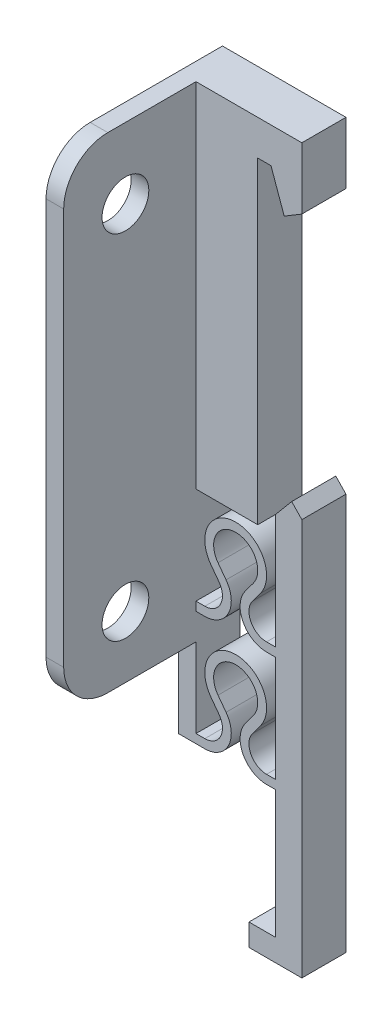
SolidWorks part; units mm, degrees
ref_plane "Front Plane" through (0, 0, 0) normal (0, 0, 1) x (1, 0, 0)
ref_plane "Top Plane" through (0, 0, 0) normal (0, 1, 0) x (1, 0, 0)
ref_plane "Right Plane" through (0, 0, 0) normal (1, 0, 0) x (0, 0, -1)
sketch "Sketch1" plane through (0, 0, 0) normal (0, 0, 1) x (1, 0, 0)
  line L0 (0, 30) -> (12, 30)
  line L1 (0, -55) -> (0, 55) construction
  line L2 (11, -41.5) -> (11, -49.5)
  line L3 (14, 23) -> (12, 21.8)
  line L4 (12, 21.8) -> (10.5, 26)
  line L5 (10.5, 26) -> (9, 26)
  line L6 (9, 26) -> (9, -10)
  line L7 (9, -10) -> (2, -10)
  line L8 (2, -10) -> (2, -12)
  line L9 (3, -21) -> (2, -21)
  line L10 (11, -18.3) -> (11, -8)
  line L11 (12.846, -5.8) -> (14, -7)
  line L12 (14, -7) -> (14, -37)
  line L13 (3, -22) -> (2, -22)
  line L14 (2, -35) -> (0, -35)
  line L15 (0, -35) -> (0, 30)
  line L16 (6.5, -10.2697) -> (6.5, -61.0736) construction
  line L17 (11, -19.8) -> (11, -21)
  line L18 (5.4072, -17.2096) -> (4.494, -15.9819)
  line L19 (2, -33.5) -> (2, -22)
  line L20 (55, 0) -> (-55, 0) construction
  line L21 (11, -8) -> (12.846, -5.8)
  line L22 (14, -37) -> (14, -40)
  line L23 (4.6048, -17.8064) -> (3.6916, -16.5787)
  line L24 (2, -21) -> (2, -13.5)
  line L25 (14, -40) -> (14, -43)
  line L26 (12, 30) -> (14, 30)
  line L27 (14, 30) -> (14, 23)
  line L28 (11, -49.5) -> (8, -49.5)
  line L29 (8, -49.5) -> (8, -52)
  line L30 (8, -52) -> (14, -52)
  line L31 (14, -52) -> (14, -43)
  line L32 (2, -12) -> (2, -13.5)
  line L33 (11, -18.3) -> (11, -19.8)
  line L34 (8.3952, -17.8064) -> (9.3084, -16.5787)
  line L35 (7.5928, -17.2096) -> (8.506, -15.9819)
  line L36 (10, -21) -> (11, -21)
  line L37 (10, -22) -> (11, -22)
  line L38 (11, -22) -> (11, -34)
  line L39 (11, -40) -> (11, -41.5)
  line L40 (2, -33.5) -> (2, -34)
  line L41 (5.4072, -30.2096) -> (4.494, -28.9819)
  line L42 (4.6048, -30.8064) -> (3.6916, -29.5787)
  line L43 (8.3952, -30.8064) -> (9.3084, -29.5787)
  line L44 (7.5928, -30.2096) -> (8.506, -28.9819)
  line L45 (10, -34) -> (11, -34)
  line L46 (10, -35) -> (11, -35)
  line L47 (3, -35) -> (2, -35)
  line L48 (3, -34) -> (2, -34)
  line L49 (6.5, -23.2697) -> (6.5, -74.0736) construction
  line L50 (11, -35) -> (11, -40)
  arc A0 (9.3084, -16.5787) -> (3.6916, -16.5787) centre (6.5, -14.4899) ccw
  arc A1 (8.506, -15.9819) -> (4.494, -15.9819) centre (6.5, -14.4899) ccw
  arc A2 (3, -21) -> (4.6048, -17.8064) centre (3, -19) ccw
  arc A3 (3, -22) -> (5.4072, -17.2096) centre (3, -19) ccw
  arc A4 (10, -22) -> (7.5928, -17.2096) centre (10, -19) cw
  arc A5 (10, -21) -> (8.3952, -17.8064) centre (10, -19) cw
  arc A6 (9.3084, -29.5787) -> (3.6916, -29.5787) centre (6.5, -27.4899) ccw
  arc A7 (8.506, -28.9819) -> (4.494, -28.9819) centre (6.5, -27.4899) ccw
  arc A8 (3, -34) -> (4.6048, -30.8064) centre (3, -32) ccw
  arc A9 (3, -35) -> (5.4072, -30.2096) centre (3, -32) ccw
  arc A10 (10, -35) -> (7.5928, -30.2096) centre (10, -32) cw
  arc A11 (10, -34) -> (8.3952, -30.8064) centre (10, -32) cw
  dimension "D33" = 5
  dimension "D34" = 7
  dimension "D35" = 11
  dimension "D36" = 1
  dimension "D37" = 4
  dimension "D38" = 6
  dimension "D43" = 1.2
  dimension "D1" = 36
  dimension "D2" = 2
  dimension "D3" = 1.5
  dimension "D4" = 20
  dimension "D5" = 0.5
  dimension "D6" = 4
  dimension "D7" = 4.2
  dimension "D8" = 1.5
  dimension "D9" = 12
  dimension "D10" = 2
  dimension "D11" = 0
  dimension "D12" = 7
  dimension "D13" = 9
  dimension "D14" = 2
  dimension "D15" = 2
  dimension "D16" = 2
  dimension "D17" = 9
  dimension "D18" = 3
  dimension "D19" = 4.5
  dimension "D20" = 30
  dimension "D21" = 10
  dimension "D22" = 2
  dimension "D23" = 2.2
  dimension "D24" = 1.2
  dimension "D25" = 3
  dimension "D26" = 9
  dimension "D28" = 2
  dimension "D29" = 3
  dimension "D30" = 2.5
  dimension "D31" = 3
  dimension "D32" = 3
  dimension "D39" = 1
  dimension "D40" = 1
  dimension "D41" = 1.5
  dimension "D42" = 1.5
  dimension "D44" = 18
  dimension "D45" = 140
  dimension "D46" = 2
extrude "Boss-Extrude1" add sketch "Sketch1" along normal blind 5
sketch "Sketch2" plane through (0, 0, 0) normal (1, 0, 0) x (0, 0, -1)
  line L0 (0, 7.7) -> (0, -7.7) construction
  line L1 (0, 30) -> (-20, 30)
  line L2 (0, 30) -> (0, -25)
  line L3 (0, -25) -> (-20, -25)
  line L4 (-20, 30) -> (-20, -25)
  line L5 (2.75, 0) -> (-2.75, 0) construction
  dimension "D1" = 20
  dimension "D2" = 55
  dimension "D3" = 25
extrude "Boss-Extrude2" add sketch "Sketch2" along normal blind 2
fillet "Fillet1" radius 5 2 edges at (1, -25, 20) (1, 30, 20)
sketch "Sketch3" plane through (0, 0, 0) normal (1, 0, 0) x (0, 0, -1)
  line L0 (-20, -20) -> (-20, 25) construction
  line L1 (7.7, 0) -> (-7.7, 0) construction
  circle A0 centre (-13, 22) radius 2.65
  circle A1 centre (-13, -18) radius 2.65
  dimension "D1" = 5.3
  dimension "D2" = 5.3
  dimension "D3" = 7
  dimension "D4" = 7
  dimension "D5" = 22
  dimension "D6" = 18
extrude "Cut-Extrude1" cut sketch "Sketch3" along normal up to next
